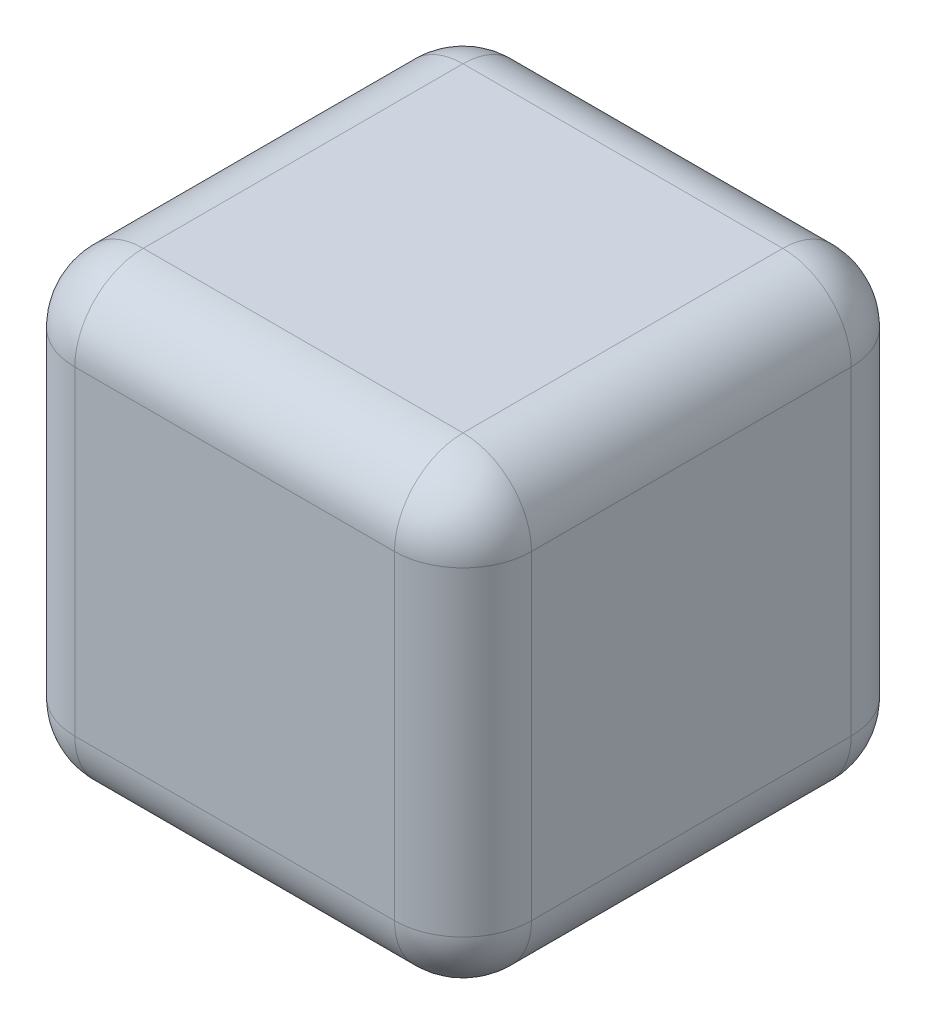
SolidWorks part; units mm, degrees
ref_plane "Front Plane" through (0, 0, 0) normal (0, 0, 1) x (1, 0, 0)
ref_plane "Top Plane" through (0, 0, 0) normal (0, 1, 0) x (1, 0, 0)
ref_plane "Right Plane" through (0, 0, 0) normal (1, 0, 0) x (0, 0, -1)
sketch "Sketch1" plane through (0, 0, 0) normal (0, 0, 1) x (1, 0, 0)
  line L1 (-50, -50) -> (50, -50)
  line L2 (-50, -50) -> (-50, 50)
  line L3 (-50, 50) -> (50, 50)
  line L4 (50, -50) -> (50, 50)
  line L5 (-50, -50) -> (50, 50) construction
  line L6 (-50, 50) -> (50, -50) construction
  point P0 (0, 0)
  dimension "D1" = 100
  dimension "D2" = 100
extrude "Boss-Extrude1" add sketch "Sketch1" along normal mid plane 100
fillet "Fillet1" radius 15 12 edges at (-50, -50, 0) (-50, 0, -50) (0, -50, -50) (50, -50, 0) (50, 0, -50) (50, 50, 0) (-50, 50, 0) (0, 50, -50) (0, -50, 50) (-50, 0, 50) (0, 50, 50) (50, 0, 50)
